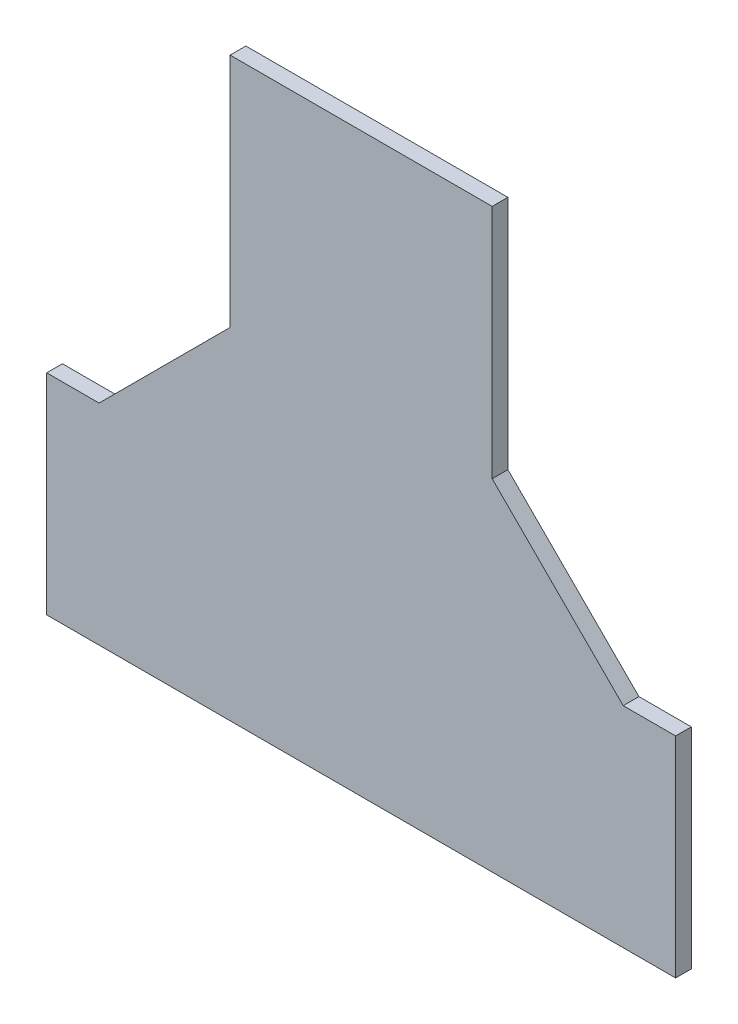
SolidWorks part; units mm, degrees
material "Thornel VCB-20 碳布"
ref_plane "前视基准面" through (0, 0, 0) normal (0, 0, 1) x (1, 0, 0)
ref_plane "上视基准面" through (0, 0, 0) normal (0, 1, 0) x (1, 0, 0)
ref_plane "右视基准面" through (0, 0, 0) normal (1, 0, 0) x (0, 0, -1)
other "Configuration Table"
sketch "草图1" plane through (0, 0, 0) normal (0, 0, 1) x (1, 0, 0)
  line L9 (0, 0) -> (0, 40)
  line L14 (0, 40) -> (10, 40)
  line L15 (10, 40) -> (35, 65)
  line L16 (35, 65) -> (35, 110)
  line L17 (35, 110) -> (85, 110)
  line L18 (85, 110) -> (85, 65)
  line L19 (85, 65) -> (110, 40)
  line L20 (110, 40) -> (120, 40)
  line L21 (120, 40) -> (120, 0)
  line L22 (120, 0) -> (0, 0)
  line L23 (35, 65) -> (85, 65) construction
  point P2 (87.7523, 40)
  point P12 (92.5846, 93.1898)
  point P13 (56.1354, 67.0127)
  dimension "D1" = 40
  dimension "D2" = 50
  dimension "D3" = 135
  dimension "D4" = 135
  dimension "D5" = 110
  dimension "D6" = 25
  dimension "D7" = 10
extrude "凸台-拉伸1" add sketch "草图1" along normal blind 3
